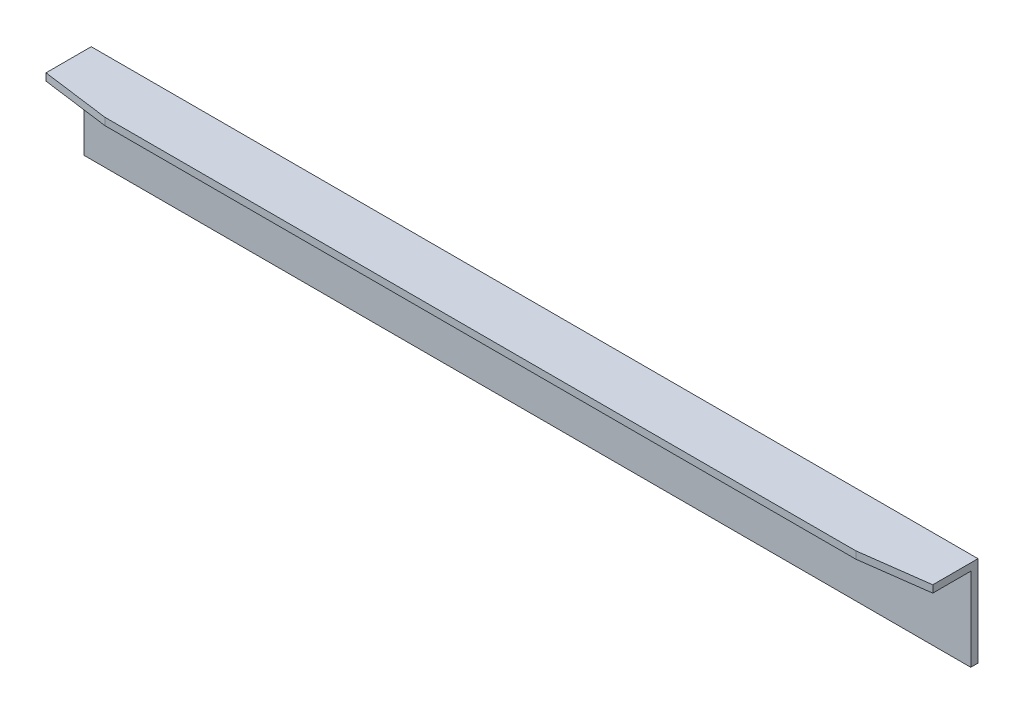
SolidWorks part; units mm, degrees
material "PW90:Mi:0:31:Ar:0:-1:Sc:1:So:2:Re:16:Ts:17:18:19:20:21:22:"
ref_plane "前视" through (0, 0, 0) normal (0, 0, 1) x (1, 0, 0)
ref_plane "上视" through (0, 0, 0) normal (0, 1, 0) x (1, 0, 0)
ref_plane "右视" through (0, 0, 0) normal (1, 0, 0) x (0, 0, -1)
sketch "草图1" plane through (0, 0, 0) normal (0, 0, 1) x (1, 0, 0)
  line L0 (0, 0) -> (0, 213.0221) construction
  line L1 (0, 213.0221) -> (0, 106) construction
  line L2 (210, 146) -> (980, 146) construction
  line L3 (-980, 200) -> (980, 200)
  line L4 (-980, 200) -> (-980, 0)
  line L5 (-980, 0) -> (980, 0)
  line L6 (980, 200) -> (980, 0)
  line L8 (930, 159) -> (930, 17.8164) construction
  line L9 (980, 34) -> (210, 34) construction
  line L10 (890, 175.3513) -> (890, 17.8164) construction
  line L11 (850, 159) -> (850, 17.8164) construction
  line L12 (810, 175.3513) -> (810, 17.8164) construction
  line L13 (770, 175.3513) -> (770, 17.8164) construction
  line L14 (730, 175.3513) -> (730, 17.8164) construction
  line L15 (0, 0) -> (330, 0) construction
  line L16 (0, 0) -> (1632.9772, 0) construction
  line L17 (-980, 106) -> (980, 106) construction
  line L18 (650, 175.3513) -> (650, 17.8164) construction
  line L19 (690, 175.3513) -> (690, 17.8164) construction
  line L20 (550, 175.3513) -> (550, 17.8164) construction
  line L21 (450, 293.2849) -> (450, -102.0826) construction
  line L22 (370, 293.2849) -> (370, -134.4898) construction
  line L23 (290, 293.2849) -> (290, -79.3976) construction
  line L24 (210, 293.2849) -> (210, -79.3976) construction
  line L25 (130, 293.2849) -> (130, -79.3976) construction
  line L26 (410, 320.2436) -> (410, -207.8775) construction
  dimension "D1" = 200
  dimension "D2" = 1960
  dimension "D3" = 54
  dimension "D6" = 50
  dimension "D7" = 40
  dimension "D8" = 80
  dimension "D9" = 80
  dimension "D10" = 80
  dimension "D11" = 80
  dimension "D13" = 80
  dimension "D14" = 80
  dimension "D15" = 100
  dimension "D19" = 530
  dimension "D20" = 80
  dimension "D21" = 80
  dimension "D22" = 80
  dimension "D23" = 80
  dimension "D24" = 40
extrude "基体-拉伸" add sketch "草图1" along normal blind 16
sketch "草图2" plane through (0, 0, 16) normal (0, 0, 1) x (1, 0, 0)
  line L0 (0, 0) -> (0, 345.2694) construction
  line L1 (980, 0) -> (980, 200) construction
  line L2 (-980, 200) -> (980, 200)
  line L3 (-980, 200) -> (-980, 184)
  line L4 (-980, 184) -> (980, 184)
  line L5 (980, 200) -> (980, 184)
  dimension "D1" = 16
extrude "凸台-拉伸1" add sketch "草图2" along normal blind 104
sketch "草图3" plane through (0, 200, 0) normal (0, 1, 0) x (-1, 0, 0)
  line L0 (-277.803, 48) -> (-964.3408, 48) construction
  line L1 (-980, 120) -> (980, 120) construction
  line L2 (-980, 120) -> (-980, 0) construction
  line L3 (-980, 100) -> (-830, 120)
  line L4 (-277.803, 48) -> (7.9594, 48) construction
  line L5 (0, 0) -> (0, 96) construction
  line L6 (980, 100) -> (830, 120)
  line L7 (-830, 120) -> (-980, 120)
  line L8 (-980, 120) -> (-980, 100)
  line L9 (830, 120) -> (980, 120)
  line L11 (980, 120) -> (980, 100)
  point P4 (-830, 120)
  point P5 (-980, 100)
  dimension "D1" = 72
  dimension "D2" = 150
  dimension "D3" = 20
extrude "切除-拉伸1" cut sketch "草图3" against normal through all
